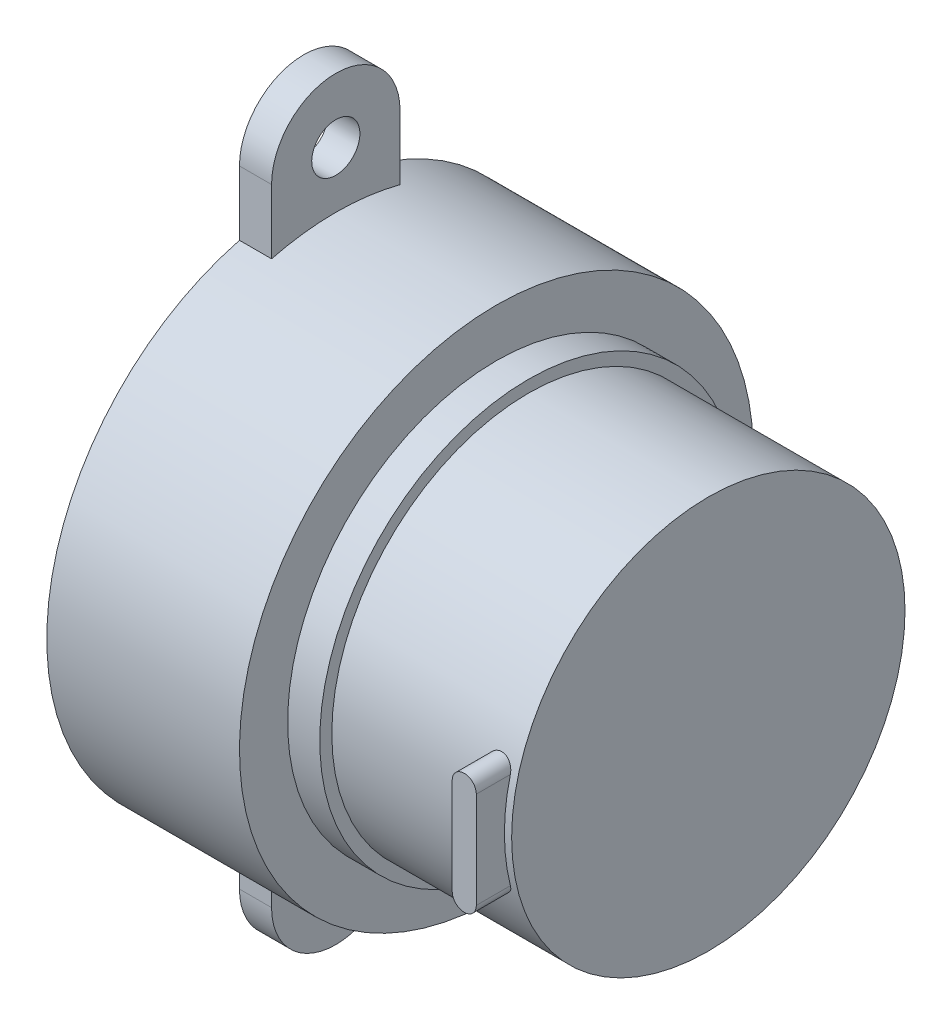
SolidWorks part; units mm, degrees
ref_plane "前视基准面" through (0, 0, 0) normal (0, 0, 1) x (1, 0, 0)
ref_plane "上视基准面" through (0, 0, 0) normal (0, 1, 0) x (1, 0, 0)
ref_plane "右视基准面" through (0, 0, 0) normal (1, 0, 0) x (0, 0, -1)
other "Configuration Table"
sketch "草图1" plane through (0, 0, 0) normal (0, 0, 1) x (1, 0, 0)
  line L14 (0, 0) -> (0, 16)
  line L15 (0, 16) -> (12, 16)
  line L16 (12, 16) -> (12, 13)
  line L17 (12, 13) -> (14, 13)
  line L18 (14, 13) -> (14, 12.25)
  line L19 (14, 12.25) -> (25.2, 12.25)
  line L20 (25.2, 12.25) -> (25.2, 0)
  line L21 (25.2, 0) -> (0, 0) construction
  line L22 (0, 0) -> (25.2, 0)
  point P9 (14, 12.625)
  dimension "D1" = 32
  dimension "D2" = 26
  dimension "D3" = 2
  dimension "D4" = 24.5
  dimension "D5" = 12
  dimension "D6" = 25.2
revolve "旋转1" add sketch "草图1" angle 360 about L21
sketch "草图2" plane through (0, 0, 0) normal (-1, 0, 0) x (0, 0, 1)
  line L0 (0, 19.5) -> (0, -19.5) construction
  line L1 (4, 19.5) -> (4, -19.5)
  line L2 (-4, 19.5) -> (-4, -19.5)
  arc A4 (4, 19.5) -> (-4, 19.5) centre (0, 19.5) ccw
  arc A5 (-4, -19.5) -> (4, -19.5) centre (0, -19.5) ccw
  circle A6 centre (0, 19.5) radius 1.5
  circle A7 centre (0, -19.5) radius 1.5
  point P3 (0, 0)
  dimension "D2" = 3
  dimension "D3" = 3
  dimension "D1" = 8
  dimension "D4" = 39
extrude "凸台-拉伸1" add sketch "草图2" against normal blind 2
ref_plane "基准面1" through (0, 0, -8) normal (0, 0, 1) x (1, 0, 0)
sketch "草图4" plane through (0, 0, -8) normal (0, 0, 1) x (1, 0, 0)
  line L0 (0, 0) -> (0, 4.25)
  line L1 (0, 15.4919) -> (0, -15.4919) construction
  line L2 (0, 4.25) -> (-0.5, 4.25)
  line L3 (-0.5, 4.25) -> (-0.5, 4)
  line L4 (-0.5, 4) -> (-2.7, 4)
  line L5 (-2.7, 4) -> (-2.7, 2.5)
  line L6 (-2.7, 2.5) -> (-10.2, 2.5)
  line L7 (-10.2, 2.5) -> (-10.2, 0)
  line L10 (-10.2, 0) -> (0, 0) construction
  line L11 (0, 0) -> (-10.2, 0)
  point P5 (-0.25, 4.25)
  dimension "D1" = 8.5
  dimension "D2" = 8
  dimension "D3" = 5
  dimension "D4" = 2.7
  dimension "D5" = 0.5
  dimension "D6" = 10.2
revolve "旋转2" add sketch "草图4" angle 360 about L10
hole_wizard "M3 螺纹孔2" positions "草图7" profile "草图8" tap size "M3" standard "GB"
sketch "草图7" plane through (-10.2, 0, 0) normal (-1, 0, 0) x (0, 0, 1)
  point P0 (-8, 0)
cosmetic thread "孔螺蚊线2" parameters "D1"=6, "D2"=3
sketch "草图8" plane through (-10.2, 0, -8) normal (0, 1, 0) x (0, 0, 1)
  line L0 (0, 0) -> (0, 6.7511)
  line L1 (0, 6.7511) -> (1.25, 6)
  line L2 (1.25, 6) -> (1.25, 0)
  line L5 (1.25, 0) -> (0, 0)
  line L10 (0, 6.7511) -> (-1.25, 6) construction
  line L11 (0, -6.35) -> (0, 107.95) construction
  dimension "螺纹孔钻头直径" = 2.5
  dimension "螺纹孔钻头深度" = 6
  dimension "导头角度" = 118
sketch "草图5" plane through (-10.2, 0, 0) normal (-1, 0, 0) x (0, 0, 1)
  line L0 (-8, 2.5) -> (-8, -2.3411) construction
  line L1 (-10, 1.5) -> (-10, -1.5)
  line L2 (-6, 1.5) -> (-6, -1.5)
  circle A1 centre (-8, 0) radius 2.5
  circle A2 centre (-8, 0) radius 2.5
  circle M5 centre (-8, 0) radius 2.5
  dimension "D2" = 4
  dimension "D1" = 0
extrude "切除-拉伸1" cut sketch "草图5" against normal blind 5 contours L1 M5 | L2 M5
sketch "草图9" plane through (0, 0, 0) normal (0, 0, 1) x (1, 0, 0)
  line L0 (24, 2.9959) -> (24, -3.0041) construction
  line L1 (24.75, 2.9959) -> (24.75, -3.0041)
  line L2 (23.25, 2.9959) -> (23.25, -3.0041)
  arc A0 (24.75, 2.9959) -> (23.25, 2.9959) centre (24, 2.9959) ccw
  arc A1 (23.25, -3.0041) -> (24.75, -3.0041) centre (24, -3.0041) ccw
  point P2 (24, -0.0041)
  dimension "D1" = 6
  dimension "D2" = 1.5
  dimension "D3" = 24
extrude "凸台-拉伸2" add sketch "草图9" along normal blind 14
